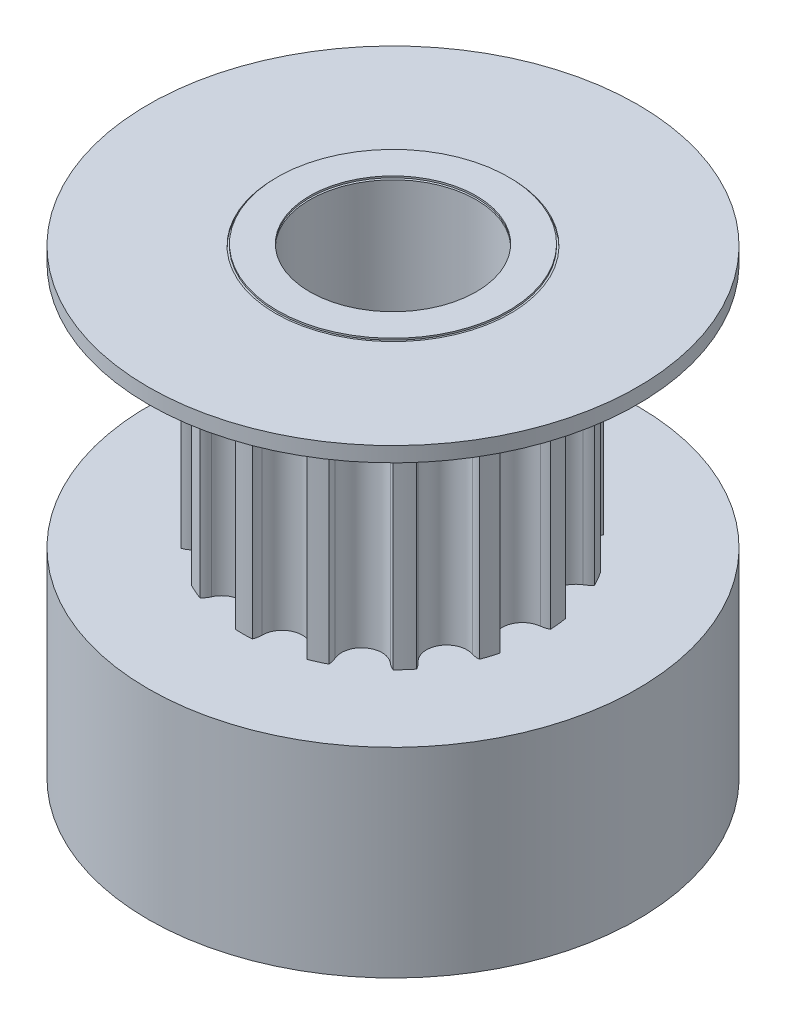
SolidWorks part; units mm, degrees
ref_plane "Front Plane" through (0, 0, 0) normal (0, 0, 1) x (1, 0, 0)
ref_plane "Top Plane" through (0, 0, 0) normal (0, 1, 0) x (1, 0, 0)
ref_plane "Right Plane" through (0, 0, 0) normal (1, 0, 0) x (0, 0, -1)
ref_plane "Plane6" through (0, 7.4, 0) normal (0, 1, 0) x (1, 0, 0)
sketch "Sketch1" plane through (0, 7.4, 0) normal (0, -1, 0) x (1, 0, 0)
  arc A0 (91.1282, 677.7517) -> (90.9137, 677.8702) centre (91.3349, 678.3789) cw
  arc A1 (90.9137, 677.8702) -> (91.0692, 678.3428) centre (95.2593, 676.7015) cw
  arc A2 (91.0692, 678.3428) -> (91.3122, 678.3108) centre (91.106, 677.6834) cw
  arc A3 (91.3122, 678.3108) -> (91.9124, 679.3412) centre (91.5026, 678.8899) ccw
  arc A4 (91.9124, 679.3412) -> (91.7647, 679.5367) centre (92.3564, 679.83) cw
  arc A5 (91.7647, 679.5367) -> (92.099, 679.9051) centre (95.2593, 676.7015) cw
  arc A6 (92.099, 679.9051) -> (92.308, 679.7771) centre (91.8644, 679.2878) cw
  arc A7 (92.308, 679.7771) -> (93.2754, 680.4742) centre (92.7174, 680.2287) ccw
  arc A8 (93.2754, 680.4742) -> (93.22, 680.713) centre (93.8799, 680.7402) cw
  arc A9 (93.22, 680.713) -> (93.6753, 680.9135) centre (95.2593, 676.7015) cw
  arc A10 (93.6753, 680.9135) -> (93.8141, 680.7116) centre (93.2098, 680.445) cw
  arc A11 (93.8141, 680.7116) -> (94.9814, 680.955) centre (94.3718, 680.9576) ccw
  arc A12 (94.9814, 680.955) -> (95.0279, 681.1956) centre (95.6418, 680.9521) cw
  arc A13 (95.0279, 681.1956) -> (95.5254, 681.1937) centre (95.2593, 676.7015) cw
  arc A14 (95.5254, 681.1937) -> (95.57, 680.9527) centre (94.9096, 680.955) cw
  arc A15 (95.57, 680.9527) -> (96.7355, 680.7003) centre (96.1796, 680.9506) ccw
  arc A16 (96.7355, 680.7003) -> (96.8758, 680.9012) centre (97.3376, 680.4291) cw
  arc A17 (96.8758, 680.9012) -> (97.3295, 680.6971) centre (95.2593, 676.7015) cw
  arc A18 (97.3295, 680.6971) -> (97.2723, 680.4588) centre (96.6699, 680.7294) cw
  arc A19 (97.2723, 680.4588) -> (98.2343, 679.7541) centre (97.8283, 680.2089) ccw
  arc A20 (98.2343, 679.7541) -> (98.4442, 679.8806) centre (98.674, 679.2615) cw
  arc A21 (98.4442, 679.8806) -> (98.7756, 679.5096) centre (95.2593, 676.7015) cw
  arc A22 (98.7756, 679.5096) -> (98.6264, 679.3152) centre (98.1862, 679.8075) cw
  arc A23 (98.6264, 679.3152) -> (99.2187, 678.2802) centre (99.0328, 678.8608) ccw
  arc A24 (99.2187, 678.2802) -> (99.4619, 678.3103) centre (99.42, 677.6512) cw
  arc A25 (99.4619, 678.3103) -> (99.6138, 677.8366) centre (95.2593, 676.7015) cw
  arc A26 (99.6138, 677.8366) -> (99.3984, 677.7197) centre (99.1965, 678.3484) cw
  arc A27 (99.3984, 677.7197) -> (99.5185, 676.5333) centre (99.5848, 677.1393) ccw
  arc A28 (99.5185, 676.5333) -> (99.7529, 676.4619) centre (99.4466, 675.8768) cw
  arc A29 (99.7529, 676.4619) -> (99.699, 675.9673) centre (95.2593, 676.7015) cw
  arc A30 (99.699, 675.9673) -> (99.4547, 675.9481) centre (99.526, 676.6046) cw
  arc A31 (99.4547, 675.9481) -> (99.0818, 674.8155) centre (99.3889, 675.3421) ccw
  arc A32 (99.0818, 674.8155) -> (99.2669, 674.6549) centre (98.7491, 674.245) cw
  arc A33 (99.2669, 674.6549) -> (99.0165, 674.225) centre (95.2593, 676.7015) cw
  arc A34 (99.0165, 674.225) -> (98.7855, 674.3068) centre (99.1177, 674.8776) cw
  arc A35 (98.7855, 674.3068) -> (97.9842, 673.4238) centre (98.4789, 673.7799) ccw
  arc A36 (97.9842, 673.4238) -> (98.088, 673.2018) centre (97.4482, 673.0379) cw
  arc A37 (98.088, 673.2018) -> (97.6844, 672.9109) centre (95.2593, 676.7015) cw
  arc A38 (97.6844, 672.9109) -> (97.5066, 673.0796) centre (98.0422, 673.4659) cw
  arc A39 (97.5066, 673.0796) -> (96.4154, 672.5988) centre (97.0122, 672.723) ccw
  arc A40 (96.4154, 672.5988) -> (96.4199, 672.3538) centre (95.7689, 672.4643) cw
  arc A41 (96.4199, 672.3538) -> (95.9329, 672.2522) centre (95.2593, 676.7015) cw
  arc A42 (95.9329, 672.2522) -> (95.8392, 672.4787) centre (96.4856, 672.6137) cw
  arc A43 (95.8392, 672.4787) -> (94.6467, 672.4833) centre (95.2425, 672.354) ccw
  arc A44 (94.6467, 672.4833) -> (94.5512, 672.2576) centre (94.0014, 672.6234) cw
  arc A45 (94.5512, 672.2576) -> (94.065, 672.3629) centre (95.2593, 676.7015) cw
  arc A46 (94.065, 672.3629) -> (94.0714, 672.6079) centre (94.7169, 672.4684) cw
  arc A47 (94.0714, 672.6079) -> (92.984, 673.0971) centre (93.4756, 672.7367) ccw
  arc A48 (92.984, 673.0971) -> (92.8049, 672.9298) centre (92.4514, 673.4876) cw
  arc A49 (92.8049, 672.9298) -> (92.4036, 673.2238) centre (95.2593, 676.7015) cw
  arc A50 (92.4036, 673.2238) -> (92.5091, 673.4449) centre (93.042, 673.0549) cw
  arc A51 (92.5091, 673.4449) -> (91.7146, 674.3342) centre (92.0171, 673.8049) ccw
  arc A52 (91.7146, 674.3342) -> (91.483, 674.2542) centre (91.3869, 674.9075) cw
  arc A53 (91.483, 674.2542) -> (91.2359, 674.6859) centre (95.2593, 676.7015) cw
  arc A54 (91.2359, 674.6859) -> (91.4223, 674.8451) centre (91.7505, 674.272) cw
  arc A55 (91.4223, 674.8451) -> (91.0582, 675.9806) centre (91.1193, 675.3741) ccw
  arc A56 (91.0582, 675.9806) -> (90.814, 676.0017) centre (90.992, 676.6377) cw
  arc A57 (90.814, 676.0017) -> (90.7639, 676.4967) centre (95.2593, 676.7015) cw
  arc A58 (90.7639, 676.4967) -> (90.9989, 676.5662) centre (91.0657, 675.9092) cw
  arc A59 (90.9989, 676.5662) -> (91.1282, 677.7517) centre (90.9373, 677.1727) ccw
extrude "Boss-Extrude1" add sketch "Sketch1" along normal blind 7.4
ref_plane "Plane1" through (0, 0, 0) normal (0, 1, 0) x (1, 0, 0)
sketch "Sketch2" plane through (0, 0, 0) normal (0, 1, 0) x (1, 0, 0)
  circle A0 centre (95.2593, -676.7015) radius 7.35
extrude "Boss-Extrude2" add sketch "Sketch2" against normal blind 6
sketch "Sketch3" plane through (0, -6, 0) normal (0, -1, 0) x (1, 0, 0)
  line L0 (96.041, 679.0762) -> (96.6268, 678.8833)
  line L1 (96.6268, 678.8833) -> (96.6026, 678.81)
  arc A0 (96.6026, 678.81) -> (96.041, 679.0762) centre (95.2593, 676.7015) cw
extrude "Boss-Extrude3" add sketch "Sketch3" along normal blind 1.5
sketch "Sketch4" plane through (0, -6, 0) normal (0, -1, 0) x (1, 0, 0)
  line L0 (93.2703, 678.2161) -> (92.9901, 678.3083)
  line L1 (92.9901, 678.3083) -> (92.4752, 676.7443)
  line L2 (92.4752, 676.7443) -> (92.7598, 676.6507)
  arc A0 (92.7598, 676.6507) -> (93.2703, 678.2161) centre (95.2593, 676.7015) cw
extrude "Cut-Extrude1" cut sketch "Sketch4" against normal blind 0.1
sketch "Sketch5" plane through (0, -7.5, 0) normal (0, -1, 0) x (1, 0, 0)
  line L0 (96.6026, 678.81) -> (96.6268, 678.8833)
  line L1 (96.6268, 678.8833) -> (96.041, 679.0762)
  line L2 (93.9835, 678.8515) -> (96.535, 678.8515)
  arc A0 (96.535, 678.8515) -> (96.6026, 678.81) centre (95.2593, 676.7015) cw
  arc A1 (96.041, 679.0762) -> (93.9835, 678.8515) centre (95.2593, 676.7015) ccw
extrude "Cut-Extrude2" cut sketch "Sketch5" against normal blind 1.6
sketch "Sketch6" plane through (0, -5.9, 0) normal (0, -1, 0) x (1, 0, 0)
  line L0 (93.9835, 678.8515) -> (96.535, 678.8515)
  arc A0 (96.535, 678.8515) -> (93.9835, 678.8515) centre (95.2593, 676.7015) ccw
extrude "Cut-Extrude3" cut sketch "Sketch6" against normal blind 13.4
sketch "Sketch7" plane through (0, -6, 0) normal (0, -1, 0) x (1, 0, 0)
  line L0 (96.041, 679.0762) -> (95.7156, 679.1833)
  line L1 (95.7156, 679.1833) -> (95.7083, 679.1609)
  arc A0 (95.7083, 679.1609) -> (96.041, 679.0762) centre (95.2593, 676.7015) cw
extrude "Cut-Extrude4" cut sketch "Sketch7" against normal blind 0.1
sketch "Sketch8" plane through (0, 7.4, 0) normal (0, 1, 0) x (-1, 0, 0)
  circle A0 centre (-95.2593, 676.7015) radius 7.35
  circle A1 centre (-95.2593, 676.7015) radius 7.35
  circle A2 centre (-95.2593, 676.7015) radius 7.35
  dimension "D1" = 0
extrude "Boss-Extrude4" add sketch "Sketch8" along normal blind 0.45 contours A0
sketch "Sketch9" plane through (0, 7.85, 0) normal (0, 1, 0) x (1, 0, 0)
  circle A0 centre (95.2593, -676.7015) radius 3.5254
extrude "Cut-Extrude5" cut sketch "Sketch9" against normal blind 0.0508
ref_plane "Plane2" through (0, 0, 676.7015) normal (0, 0, -1) x (-1, 0, 0)
sketch "Sketch10" plane through (0, 0, 676.7015) normal (0, 0, -1) x (-1, 0, 0)
  line L0 (-98.7339, 7.85) -> (-95.2593, 7.85)
  line L1 (-95.2593, 7.85) -> (-95.2593, 12.1008)
  line L2 (-95.2593, 12.1008) -> (-97.7593, 12.1008)
  line L3 (-97.7593, 12.1008) -> (-97.7593, 7.9008)
  line L4 (-97.7593, 7.9008) -> (-98.7339, 7.9008)
  line L5 (-98.7339, 7.9008) -> (-98.7339, 7.85)
  line L6 (-95.2593, 7.85) -> (-95.2593, 12.1008) construction
revolve "Revolve1" add sketch "Sketch10" angle 360 about L6
sketch "Sketch13" plane through (0, -7.5, 0) normal (0, -1, 0) x (1, 0, 0)
  circle A0 centre (95.2593, 676.7015) radius 2.5
extrude "Cut-Extrude6" cut sketch "Sketch13" against normal through all
ref_plane "Plane3" through (0, 3.2, 0) normal (0, 1, 0) x (1, 0, 0)
